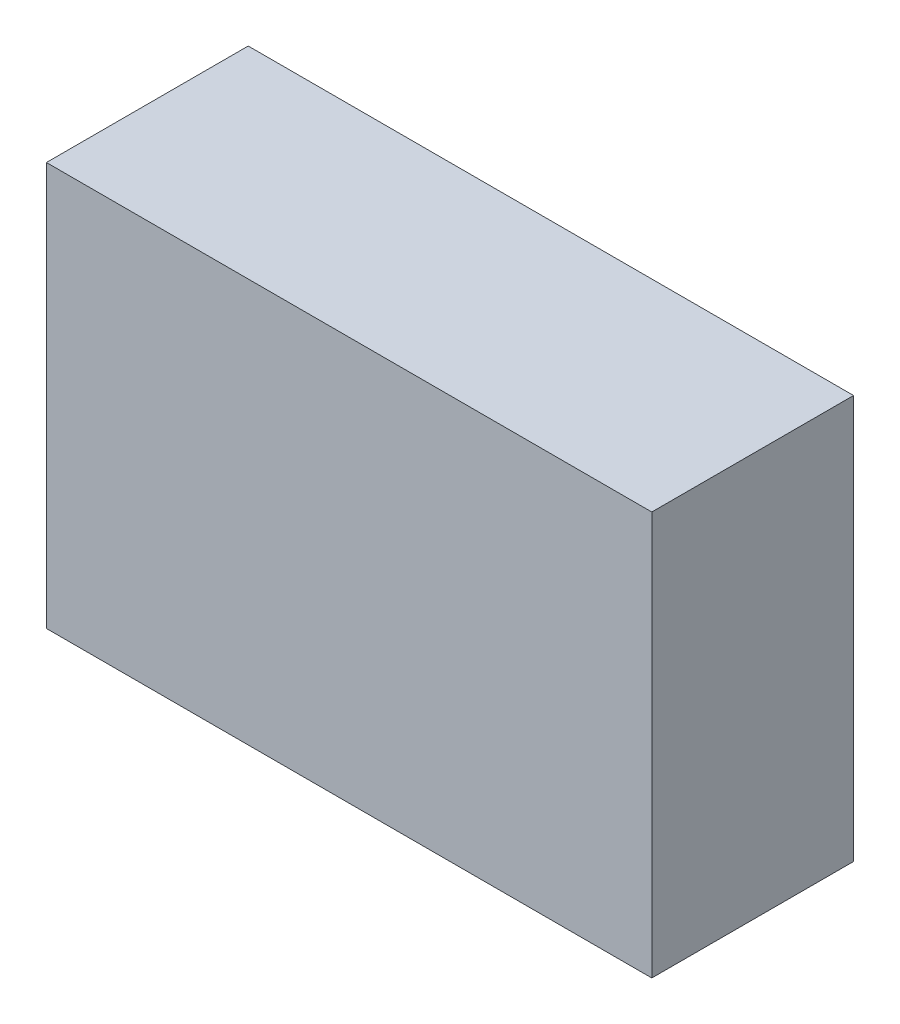
SolidWorks part; units mm, degrees
ref_plane "Front Plane" through (0, 0, 0) normal (0, 0, 1) x (1, 0, 0)
ref_plane "Top Plane" through (0, 0, 0) normal (0, 1, 0) x (1, 0, 0)
ref_plane "Right Plane" through (0, 0, 0) normal (1, 0, 0) x (0, 0, -1)
sketch "Sketch1" plane through (0, 0, 0) normal (0, 1, 0) x (1, 0, 0)
  line L1 (0, 0) -> (152.4, 0)
  line L2 (0, 0) -> (0, 50.8)
  line L3 (0, 50.8) -> (152.4, 50.8)
  line L4 (152.4, 0) -> (152.4, 50.8)
  dimension "D1" = 152.4
  dimension "D2" = 50.8
extrude "Boss-Extrude1" add sketch "Sketch1" along normal blind 101.6
